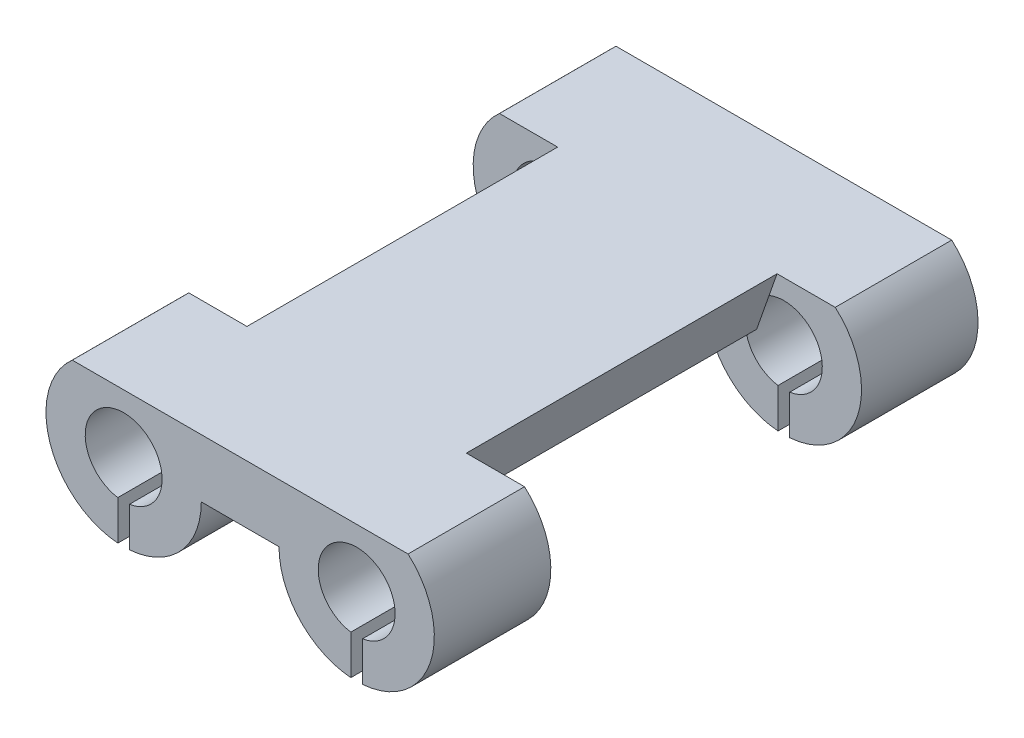
SolidWorks part; units mm, degrees
ref_plane "Front Plane" through (0, 0, 0) normal (0, 0, 1) x (1, 0, 0)
ref_plane "Top Plane" through (0, 0, 0) normal (0, 1, 0) x (1, 0, 0)
ref_plane "Right Plane" through (0, 0, 0) normal (1, 0, 0) x (0, 0, -1)
sketch "Sketch2" plane through (0, 0, 0) normal (0, 0, 1) x (1, 0, 0)
  line L0 (-15, 0) -> (15, 0) construction
  line L1 (-5, 10) -> (-15, 10)
  line L2 (-5, 10) -> (5, 10)
  line L3 (5, 10) -> (15, 10)
  line L4 (-5, 0) -> (5, 0)
  line L5 (-5, 10) -> (-5, 0) construction
  line L6 (5, 0) -> (5, 10) construction
  arc A0 (-15, 10) -> (-5, 0) centre (-15, 0) ccw
  arc A1 (5, 0) -> (15, 10) centre (15, 0) ccw
  arc A2 (-15, 10) -> (-5, 0) centre (-15, 0) cw construction
  arc A3 (15, 10) -> (5, 0) centre (15, 0) ccw construction
  dimension "D1" = 20
  dimension "D2" = 30
  dimension "D3" = 10
extrude "Boss-Extrude1" add sketch "Sketch2" along normal blind 15
sketch "Sketch3" plane through (0, 0, 15) normal (0, 0, 1) x (1, 0, 0)
  line L1 (-5, 0) -> (5, 0) construction
  line L2 (-15, 10) -> (15, 10) construction
  line L3 (-15, 10) -> (-15, 0) construction
  line L4 (-15, 0) -> (15, 0) construction
  line L5 (15, 10) -> (15, 0) construction
  line L6 (-11.5, 0) -> (-15, 10)
  line L7 (-11.5, 10) -> (11.5, 10) construction
  line L8 (-11.5, 10) -> (-11.5, 0) construction
  line L9 (-11.5, 0) -> (11.5, 0) construction
  line L10 (11.5, 10) -> (11.5, 0) construction
  line L11 (-15, 10) -> (15, 10)
  line L12 (15, 10) -> (11.5, 0)
  line L13 (11.5, 0) -> (-11.5, 0)
  dimension "D1" = 3.5
  dimension "D2" = 3.5
extrude "Boss-Extrude2" add sketch "Sketch3" along normal blind 40
sketch "Sketch4" plane through (0, 0, 55) normal (0, 0, 1) x (1, 0, 0)
  line L0 (-15, 0) -> (15, 0) construction
  line L1 (-5, 10) -> (-15, 10)
  line L2 (-5, 10) -> (5, 10)
  line L3 (5, 10) -> (15, 10)
  line L4 (-5, 0) -> (5, 0)
  line L5 (-5, 10) -> (-5, 0) construction
  line L6 (5, 0) -> (5, 10) construction
  arc A0 (-15, 10) -> (-5, 0) centre (-15, 0) ccw
  arc A1 (5, 0) -> (15, 10) centre (15, 0) ccw
  arc A2 (-15, 10) -> (-5, 0) centre (-15, 0) cw construction
  arc A3 (15, 10) -> (5, 0) centre (15, 0) ccw construction
  dimension "D1" = 20
  dimension "D2" = 30
  dimension "D3" = 10
extrude "Boss-Extrude3" add sketch "Sketch4" along normal blind 15
sketch "Sketch5" plane through (0, 0, 0) normal (0, 0, -1) x (-1, 0, 0)
  circle A0 centre (15, 0) radius 4.95
  circle A1 centre (-15, 0) radius 4.95
  dimension "D1" = 9.9
extrude "Cut-Extrude1" cut sketch "Sketch5" against normal up to vertex (15 mm away) up to point (-11.5, 0, 15)
sketch "Sketch6" plane through (0, 0, 70) normal (0, 0, 1) x (1, 0, 0)
  circle A0 centre (-15, 0) radius 4.95
  circle A1 centre (15, 0) radius 4.95
  dimension "D1" = 9.9
extrude "Cut-Extrude2" cut sketch "Sketch6" against normal up to vertex (15 mm away)
sketch "Sketch7" plane through (0, 0, 70) normal (0, 0, 1) x (1, 0, 0)
  line L0 (-15.75, 0) -> (-14.25, 0)
  line L1 (-15.75, 0) -> (-15.75, -10)
  line L2 (-14.25, 0) -> (-14.25, -10)
  line L3 (-15.75, -10) -> (-14.25, -10)
  line L4 (14.25, 0) -> (15.75, 0)
  line L5 (14.25, 0) -> (14.25, -10)
  line L6 (15.75, 0) -> (15.75, -10)
  line L7 (14.25, -10) -> (15.75, -10)
  arc A0 (-15, 10) -> (-5, 0) centre (-15, 0) ccw construction
  arc A1 (5, 0) -> (15, 10) centre (15, 0) ccw construction
  point P0 (-15, 0)
  point P9 (15, 0)
  dimension "D1" = 1.5
extrude "Cut-Extrude3" cut sketch "Sketch7" against normal through all
sketch "Sketch8" plane through (0, 0, 0) normal (0, 0, -1) x (-1, 0, 0)
  line L0 (-15, 10) -> (15, 10) construction
  line L1 (25, 10) -> (-25, 10)
  line L2 (25, 10) -> (25, 7.5)
  line L3 (25, 7.5) -> (-25, 7.5)
  line L4 (-25, 10) -> (-25, 7.5)
  arc A0 (-15, 10) -> (-15.75, -9.9718) centre (-15, 0) ccw construction
  arc A1 (15.75, -9.9718) -> (15, 10) centre (15, 0) ccw construction
  dimension "D1" = 2.5
extrude "Cut-Extrude4" cut sketch "Sketch8" against normal through all
